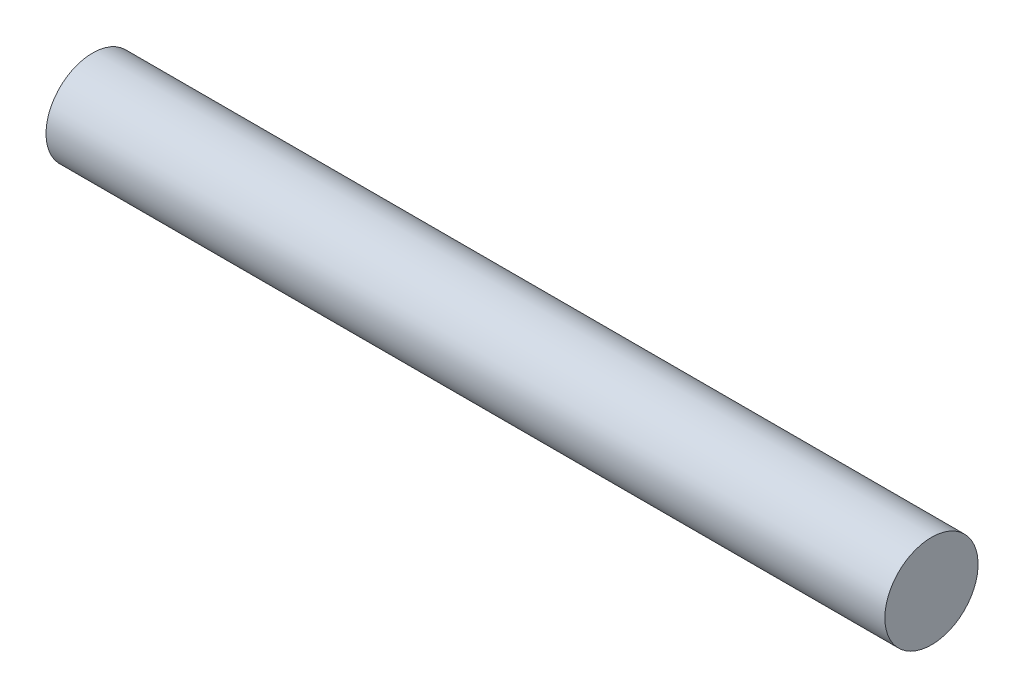
SolidWorks part; units mm, degrees
material "AISI 304"
ref_plane "Front Plane" through (0, 0, 0) normal (0, 0, 1) x (1, 0, 0)
ref_plane "Top Plane" through (0, 0, 0) normal (0, 1, 0) x (1, 0, 0)
ref_plane "Right Plane" through (0, 0, 0) normal (1, 0, 0) x (0, 0, -1)
sketch "Sketch1" plane through (0, 0, 0) normal (1, 0, 0) x (0, 0, -1)
  circle A0 centre (0, 0) radius 2.5
  dimension "D1" = 5
extrude "Boss-Extrude1" add sketch "Sketch1" along normal mid plane 45
cosmetic thread "Cosmetic Thread1" parameters "D1"=4, "D2"=4.11
cosmetic thread "Cosmetic Thread2" parameters "D1"=16, "D2"=4.11
